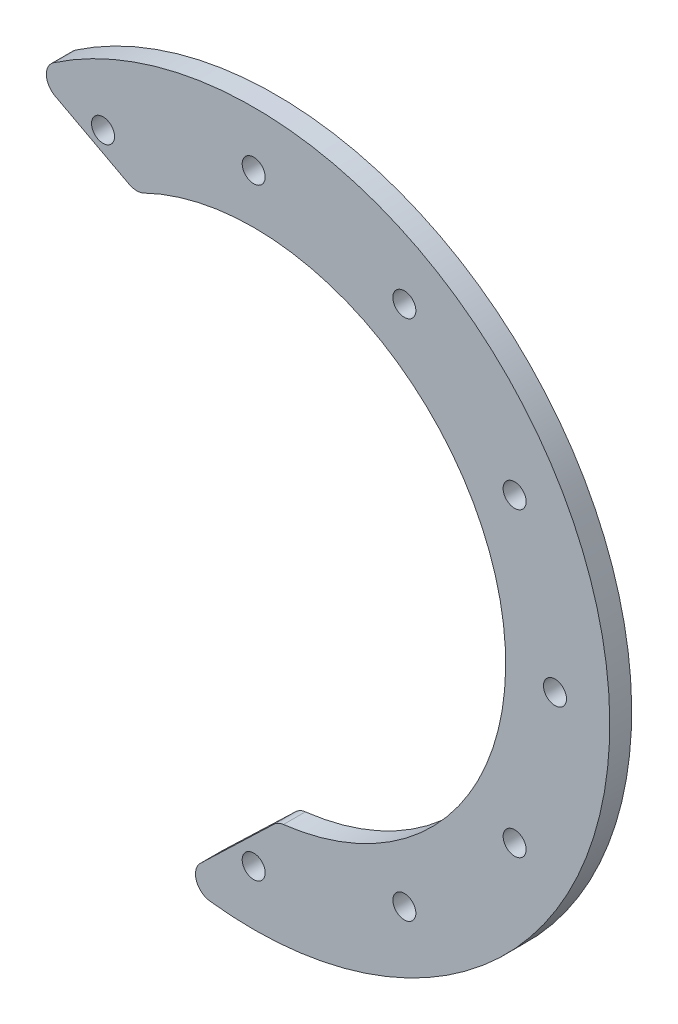
SolidWorks part; units mm, degrees
material "Thornel Mat VMA"
ref_plane "前视基准面" through (0, 0, 0) normal (0, 0, 1) x (1, 0, 0)
ref_plane "上视基准面" through (0, 0, 0) normal (0, 1, 0) x (1, 0, 0)
ref_plane "右视基准面" through (0, 0, 0) normal (1, 0, 0) x (0, 0, -1)
other "Configuration Table"
sketch "草图1" plane through (0, 0, 0) normal (0, 0, 1) x (1, 0, 0)
  circle A0 centre (0, 0) radius 46
  circle A1 centre (0, 0) radius 65
  dimension "D1" = 92
  dimension "D2" = 130
extrude "凸台-拉伸1" add sketch "草图1" along normal blind 4
sketch "草图2" plane through (0, 0, 4) normal (0, 0, 1) x (1, 0, 0)
  circle A0 centre (0, 0) radius 55 construction
  circle A1 centre (0, 55) radius 2.1
  circle A2 centre (27.5, 47.6314) radius 2.1
  circle A3 centre (47.6314, 27.5) radius 2.1
  circle A4 centre (55, 0) radius 2.1
  circle A5 centre (47.6314, -27.5) radius 2.1
  circle A6 centre (27.5, -47.6314) radius 2.1
  circle A7 centre (0, -55) radius 2.1
  circle A8 centre (-27.5, -47.6314) radius 2.1
  circle A9 centre (-47.6314, -27.5) radius 2.1
  circle A10 centre (-55, 0) radius 2.1
  circle A11 centre (-47.6314, 27.5) radius 2.1
  circle A12 centre (-27.5, 47.6314) radius 2.1
  point P29 (0, 0)
  dimension "D1" = 110
  dimension "D2" = 4.2
  dimension "D3" = 12
extrude "切除-拉伸1" cut sketch "草图2" against normal blind 4
sketch "草图3" plane through (0, 0, 4) normal (0, 0, 1) x (1, 0, 0)
  line L0 (-40.4624, 50.8704) -> (27, 15)
  line L1 (27, 15) -> (-21.7285, -61.2607)
  line L2 (27, 15) -> (-76.6833, 15) construction
  line L3 (27, 15) -> (27, -62.3798) construction
  circle A1 centre (0, 0) radius 65 construction
  circle A3 centre (0, 0) radius 65
  arc A4 (-40.4624, 50.8704) -> (-21.7285, -61.2607) centre (0, 0) ccw
  dimension "D1" = 28
  dimension "D2" = 27
  dimension "D4" = 15
  dimension "D3" = 0
extrude "切除-拉伸2" cut sketch "草图3" against normal blind 4
fillet "圆角1" radius 3 4 edges at (-11.1076, -44.6388, 2) (-21.7285, -61.2607, 2) (-21.3851, 40.7268, 2) (-40.4624, 50.8704, 2)
sketch "草图4" plane through (0, 0, 4) normal (0, 0, 1) x (1, 0, 0)
  line L0 (-37.661, -86.1952) -> (4.4481, -45.7844)
  line L1 (-19.6315, -57.9789) -> (-12.2408, -46.4124) construction
  line L2 (-37.661, -86.1952) -> (-12.2408, -46.4124)
  arc A0 (-9.1182, -45.0872) -> (-20.0413, 41.4047) centre (0, 0) ccw construction
  arc A1 (-9.1182, -45.0872) -> (-12.2408, -46.4124) centre (-9.7128, -48.0277) ccw construction
  arc A2 (-9.1182, -45.0872) -> (4.4481, -45.7844) centre (0, 0) ccw
  arc A3 (-9.1182, -45.0872) -> (-12.2408, -46.4124) centre (-9.7128, -48.0277) ccw
extrude "切除-拉伸3" cut sketch "草图4" against normal blind 15
fillet "圆角2" radius 3 2 edges at (4.4481, -45.7844, 2) (-13.988, -63.477, 2)
